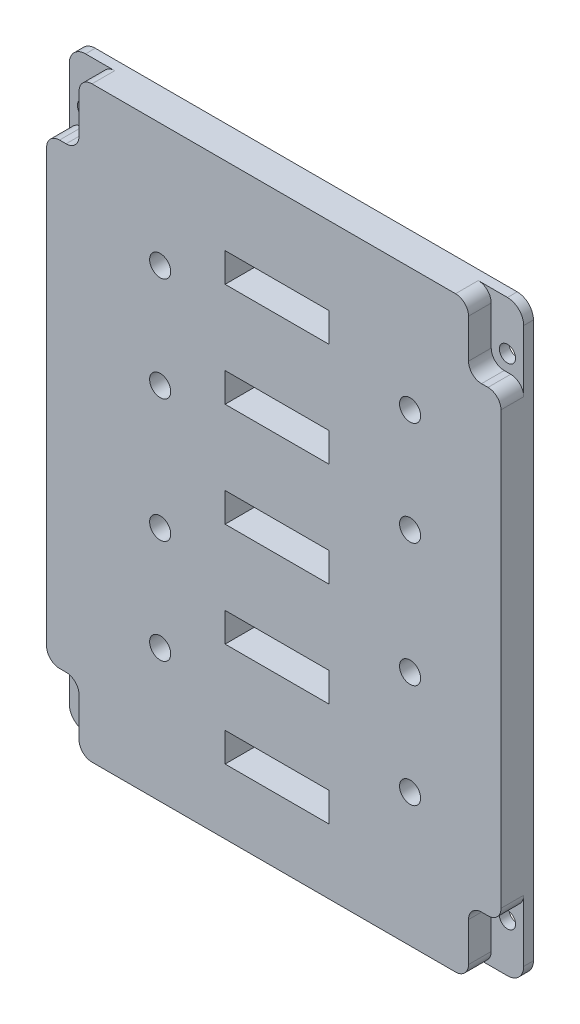
SolidWorks part; units mm, degrees
ref_plane "Front Plane" through (0, 0, 0) normal (0, 0, 1) x (1, 0, 0)
ref_plane "Top Plane" through (0, 0, 0) normal (0, 1, 0) x (1, 0, 0)
ref_plane "Right Plane" through (0, 0, 0) normal (1, 0, 0) x (0, 0, -1)
sketch "Sketch1" plane through (0, 0, 0) normal (0, 0, 1) x (1, 0, 0)
  line L1 (-67.3223, 42.6303) -> (62.6777, 42.6303)
  line L2 (-72.3223, 37.6303) -> (-72.3223, -133.3697)
  line L3 (-67.3223, -138.3697) -> (62.6777, -138.3697)
  line L4 (67.6777, 37.6303) -> (67.6777, -133.3697)
  line L5 (-17.3223, 18.6303) -> (14.6777, 18.6303)
  line L6 (-17.3223, 18.6303) -> (-17.3223, 9.6303)
  line L7 (-17.3223, 9.6303) -> (14.6777, 9.6303)
  line L8 (14.6777, 18.6303) -> (14.6777, 9.6303)
  line L9 (-17.3223, -13.3697) -> (14.6777, -13.3697)
  line L10 (-17.3223, -13.3697) -> (-17.3223, -22.3697)
  line L11 (-17.3223, -22.3697) -> (14.6777, -22.3697)
  line L12 (14.6777, -13.3697) -> (14.6777, -22.3697)
  line L13 (-17.3223, -45.3697) -> (14.6777, -45.3697)
  line L14 (-17.3223, -45.3697) -> (-17.3223, -54.3697)
  line L15 (-17.3223, -54.3697) -> (14.6777, -54.3697)
  line L16 (14.6777, -45.3697) -> (14.6777, -54.3697)
  line L17 (-17.3223, -77.3697) -> (14.6777, -77.3697)
  line L18 (-17.3223, -77.3697) -> (-17.3223, -86.3697)
  line L19 (-17.3223, -86.3697) -> (14.6777, -86.3697)
  line L20 (14.6777, -77.3697) -> (14.6777, -86.3697)
  line L21 (-17.3223, -109.3697) -> (14.6777, -109.3697)
  line L22 (-17.3223, -109.3697) -> (-17.3223, -118.3697)
  line L23 (-17.3223, -118.3697) -> (14.6777, -118.3697)
  line L24 (14.6777, -109.3697) -> (14.6777, -118.3697)
  circle A0 centre (-37.3223, 4.6303) radius 3.25
  circle A1 centre (-37.3223, -27.3697) radius 3.25
  circle A2 centre (-37.3223, -65.3697) radius 3.25
  circle A3 centre (-37.3223, -97.3697) radius 3.25
  circle A4 centre (39.6777, 4.6303) radius 3.25
  circle A5 centre (39.6777, -27.3697) radius 3.25
  circle A6 centre (39.6777, -65.3697) radius 3.25
  circle A7 centre (39.6777, -97.3697) radius 3.25
  arc A8 (67.6777, -133.3697) -> (62.6777, -138.3697) centre (62.6777, -133.3697) cw
  arc A9 (-67.3223, -138.3697) -> (-72.3223, -133.3697) centre (-67.3223, -133.3697) cw
  arc A10 (67.6777, 37.6303) -> (62.6777, 42.6303) centre (62.6777, 37.6303) ccw
  arc A11 (-72.3223, 37.6303) -> (-67.3223, 42.6303) centre (-67.3223, 37.6303) cw
  point P44 (-72.3223, -138.3697)
  point P47 (67.6777, 42.6303)
  point P50 (-72.3223, 42.6303)
  dimension "D11" = 6.5
  dimension "D12" = 6.5
  dimension "D13" = 6.5
  dimension "D14" = 6.5
  dimension "D16" = 6.5
  dimension "D17" = 6.5
  dimension "D18" = 6.5
  dimension "D19" = 6.5
  dimension "D32" = 5
  dimension "D1" = 140
  dimension "D2" = 181
  dimension "D3" = 38
  dimension "D4" = 70
  dimension "D5" = 108
  dimension "D6" = 140
  dimension "D7" = 35
  dimension "D8" = 35
  dimension "D9" = 35
  dimension "D10" = 35
  dimension "D15" = 112
  dimension "D20" = 32
  dimension "D21" = 55
  dimension "9" = 9
  dimension "D22" = 24
  dimension "D23" = 32
  dimension "D24" = 9
  dimension "D25" = 23
  dimension "D26" = 9
  dimension "D27" = 9
  dimension "D28" = 9
  dimension "D29" = 23
  dimension "D30" = 23
  dimension "D31" = 23
extrude "Boss-Extrude1" add sketch "Sketch1" along normal blind 10
sketch "Sketch2" plane through (0, 0, 10) normal (0, 0, 1) x (1, 0, 0)
  line L0 (62.6777, 42.6303) -> (-67.3223, 42.6303) construction
  line L1 (-62.3223, 42.6303) -> (-72.3223, 42.6303)
  line L2 (-62.3223, 42.6303) -> (-62.3223, 26.6303)
  line L3 (-66.3223, 22.6303) -> (-72.3223, 22.6303)
  line L4 (-72.3223, 42.6303) -> (-72.3223, 22.6303)
  line L5 (-72.3223, 37.6303) -> (-72.3223, -133.3697) construction
  line L6 (-67.3223, -138.3697) -> (62.6777, -138.3697) construction
  line L7 (-72.3223, -118.3697) -> (-66.3223, -118.3697)
  line L8 (-72.3223, -118.3697) -> (-72.3223, -138.3697)
  line L9 (-72.3223, -138.3697) -> (-62.3223, -138.3697)
  line L10 (-62.3223, -122.3697) -> (-62.3223, -138.3697)
  line L11 (67.6777, -133.3697) -> (67.6777, 37.6303) construction
  line L12 (57.6777, -138.3697) -> (67.6777, -138.3697)
  line L13 (57.6777, -138.3697) -> (57.6777, -122.3697)
  line L14 (61.6777, -118.3697) -> (67.6777, -118.3697)
  line L15 (67.6777, -138.3697) -> (67.6777, -118.3697)
  line L17 (67.6777, 22.6303) -> (61.6777, 22.6303)
  line L18 (67.6777, 22.6303) -> (67.6777, 42.6303)
  line L19 (67.6777, 42.6303) -> (57.6777, 42.6303)
  line L20 (57.6777, 26.6303) -> (57.6777, 42.6303)
  arc A0 (-66.3223, -118.3697) -> (-62.3223, -122.3697) centre (-66.3223, -122.3697) cw
  arc A1 (57.6777, -122.3697) -> (61.6777, -118.3697) centre (61.6777, -122.3697) cw
  arc A2 (57.6777, 26.6303) -> (61.6777, 22.6303) centre (61.6777, 26.6303) ccw
  arc A3 (-62.3223, 26.6303) -> (-66.3223, 22.6303) centre (-66.3223, 26.6303) cw
  point P26 (-62.3223, -118.3697)
  point P29 (57.6777, -118.3697)
  point P32 (57.6777, 22.6303)
  point P35 (-62.3223, 22.6303)
  dimension "D9" = 4
  dimension "D1" = 10
  dimension "D2" = 10
  dimension "D3" = 10
  dimension "D4" = 10
  dimension "D5" = 20
  dimension "D6" = 20
  dimension "D7" = 20
  dimension "D8" = 20
extrude "Cut-Extrude1" cut sketch "Sketch2" against normal blind 7
sketch "Sketch3" plane through (0, 0, 3) normal (0, 0, 1) x (1, 0, 0)
  line L0 (-62.3223, -138.3697) -> (-62.3223, -122.3697) construction
  line L1 (-66.3223, -118.3697) -> (-72.3223, -118.3697) construction
  line L2 (67.6777, -118.3697) -> (61.6777, -118.3697) construction
  line L3 (57.6777, -122.3697) -> (57.6777, -138.3697) construction
  line L4 (-72.3223, 22.6303) -> (-66.3223, 22.6303) construction
  line L5 (-62.3223, 26.6303) -> (-62.3223, 42.6303) construction
  line L6 (61.6777, 22.6303) -> (67.6777, 22.6303) construction
  line L7 (57.6777, 42.6303) -> (57.6777, 26.6303) construction
  circle A0 centre (-67.3223, -123.3697) radius 2.5
  circle A1 centre (62.6777, -123.3697) radius 2.5
  circle A2 centre (62.6777, 27.6303) radius 2.5
  circle A3 centre (-67.3223, 27.6303) radius 2.5
  dimension "D5" = 5
  dimension "D6" = 5
  dimension "D9" = 5
  dimension "D12" = 5
  dimension "D1" = 5
  dimension "D2" = 5
  dimension "D3" = 5
  dimension "D4" = 5
  dimension "D7" = 5
  dimension "D8" = 5
  dimension "D10" = 5
  dimension "D11" = 5
extrude "Cut-Extrude2" cut sketch "Sketch3" against normal blind 10
fillet "Fillet1" radius 4 8 edges at (-72.3223, 22.6303, 6.5) (-62.3223, 42.6303, 6.5) (57.6777, 42.6303, 6.5) (67.6777, 22.6303, 6.5) (67.6777, -118.3697, 6.5) (57.6777, -138.3697, 6.5) (-72.3223, -118.3697, 6.5) (-62.3223, -138.3697, 6.5)
